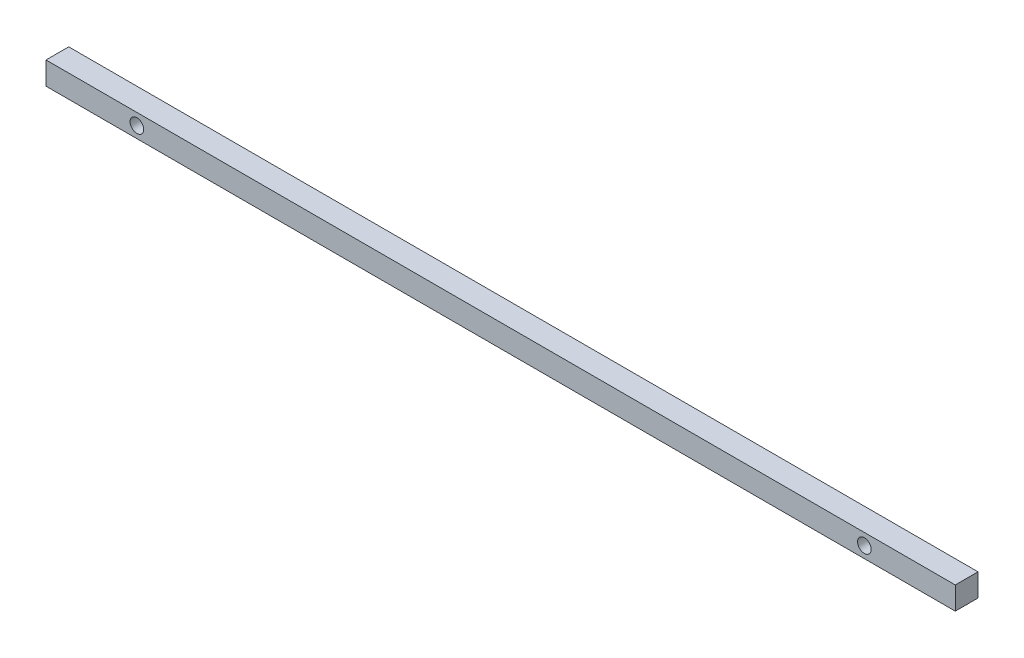
SolidWorks part; units mm, degrees
ref_plane "Alzado" through (0, 0, 0) normal (0, 0, 1) x (1, 0, 0)
ref_plane "Planta" through (0, 0, 0) normal (0, 1, 0) x (1, 0, 0)
ref_plane "Vista lateral" through (0, 0, 0) normal (1, 0, 0) x (0, 0, -1)
sketch "Croquis1" plane through (0, 0, 0) normal (0, 0, 1) x (1, 0, 0)
  line L0 (0, 0) -> (0, 10)
  line L1 (0, 10) -> (400, 10)
  line L2 (400, 10) -> (400, 0)
  line L3 (400, 0) -> (0, 0)
  circle A0 centre (40, 5) radius 3
  circle A1 centre (360, 5) radius 3
  point P9 (400, 5)
  point P10 (0, 0)
  dimension "D3" = 6
  dimension "D1" = 320
  dimension "D2" = 10
  dimension "D4" = 40
  dimension "D5" = 40
extrude "Saliente-Extruir1" add sketch "Croquis1" along normal blind 10
